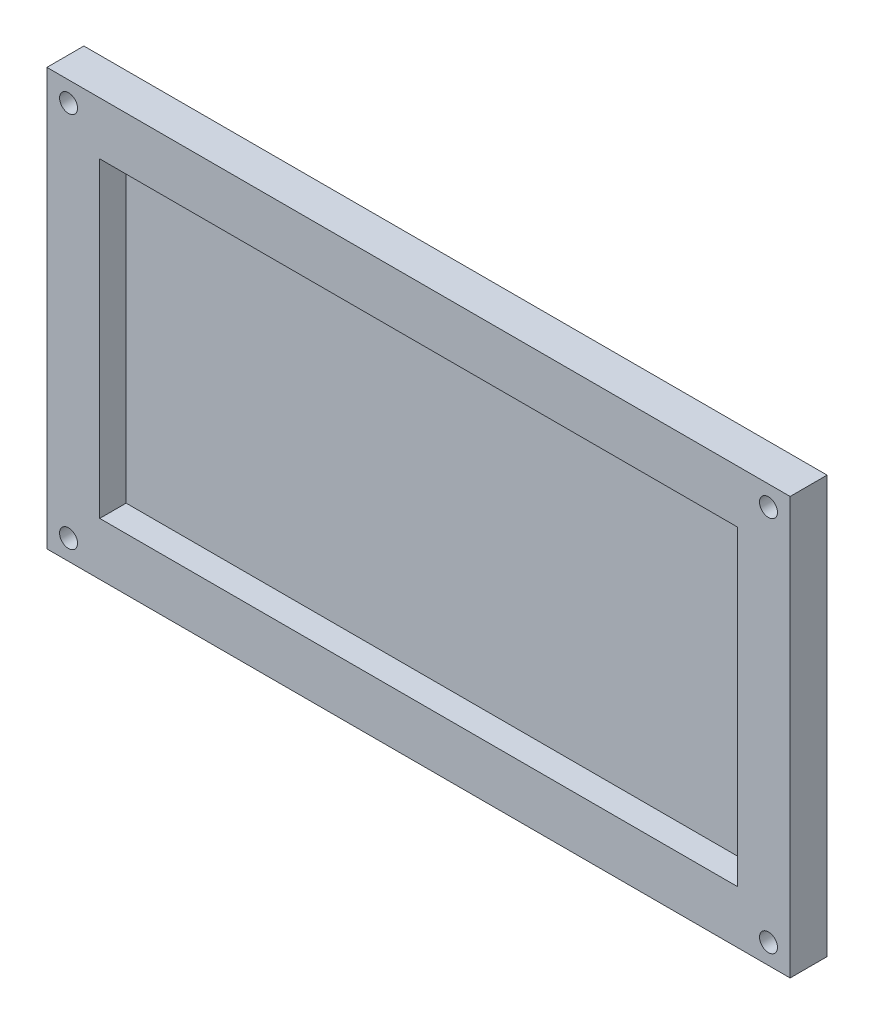
SolidWorks part; units mm, degrees
ref_plane "前视基准面" through (0, 0, 0) normal (0, 0, 1) x (1, 0, 0)
ref_plane "上视基准面" through (0, 0, 0) normal (0, 1, 0) x (1, 0, 0)
ref_plane "右视基准面" through (0, 0, 0) normal (1, 0, 0) x (0, 0, -1)
other "Configuration Table"
sketch "草图1" plane through (0, 0, 0) normal (0, 0, 1) x (1, 0, 0)
  line L0 (-70.35, 0) -> (70.35, 0) construction
  line L1 (-70.35, 39.475) -> (70.35, 39.475)
  line L2 (-70.35, 39.475) -> (-70.35, -39.475)
  line L3 (-70.35, -39.475) -> (70.35, -39.475)
  line L4 (70.35, 39.475) -> (70.35, -39.475)
  line L5 (-70.35, 39.475) -> (70.35, -39.475) construction
  line L6 (-70.35, -39.475) -> (70.35, 39.475) construction
  line L7 (0, -39.475) -> (0, 39.475) construction
  circle A0 centre (-66.2527, 35.6683) radius 1.7
  circle A1 centre (66.2527, 35.6683) radius 1.7
  circle A2 centre (66.2527, -35.6683) radius 1.7
  circle A3 centre (-66.2527, -35.6683) radius 1.7
  point P0 (0, 0)
  dimension "D1" = 78.95
  dimension "D2" = 140.7
extrude "凸台-拉伸1" add sketch "草图1" along normal blind 7
sketch "草图2" plane through (0, 0, 7) normal (0, 0, 1) x (1, 0, 0)
  line L0 (70.35, 39.475) -> (-70.35, 39.475) construction
  line L1 (-60.35, 29.475) -> (60.35, 29.475)
  line L2 (-60.35, 29.475) -> (-60.35, -29.475)
  line L3 (-60.35, -29.475) -> (60.35, -29.475)
  line L4 (60.35, 29.475) -> (60.35, -29.475)
  line L5 (-70.35, -39.475) -> (70.35, -39.475) construction
  line L6 (-70.35, 39.475) -> (-70.35, -39.475) construction
  line L7 (70.35, -39.475) -> (70.35, 39.475) construction
  dimension "D1" = 10
  dimension "D2" = 10
  dimension "D3" = 10
  dimension "D4" = 10
extrude "切除-拉伸1" cut sketch "草图2" against normal blind 5
